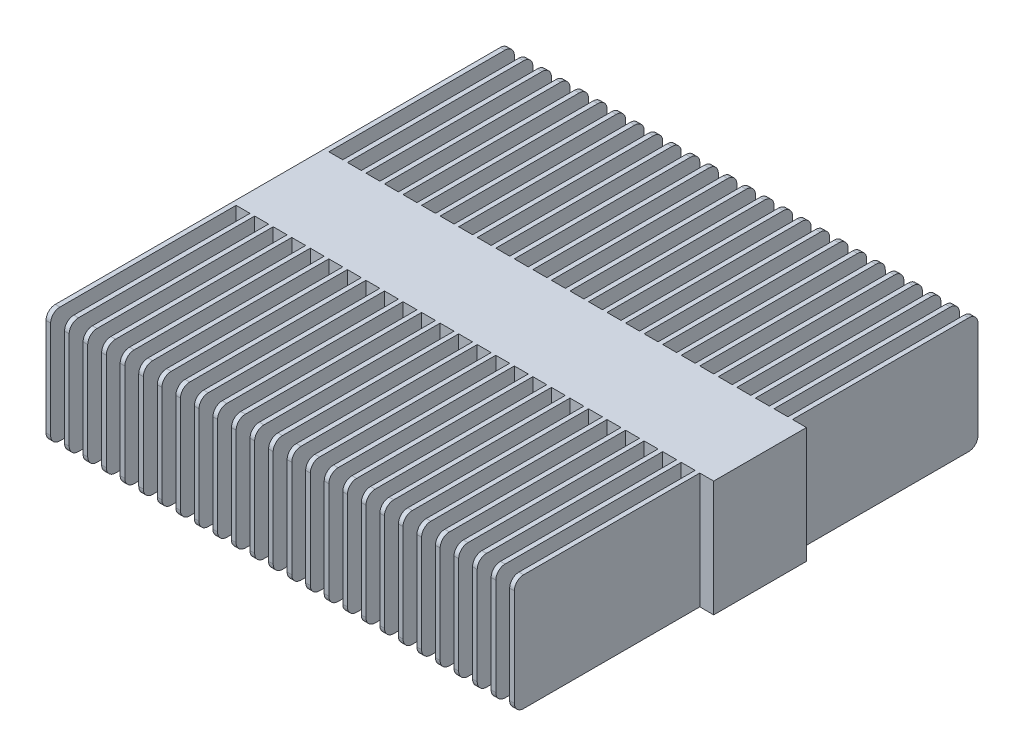
SolidWorks part; units mm, degrees
material "Thornel VCB-20 탄소 섬유"
ref_plane "정면" through (0, 0, 0) normal (0, 0, 1) x (1, 0, 0)
ref_plane "윗면" through (0, 0, 0) normal (0, 1, 0) x (1, 0, 0)
ref_plane "우측면" through (0, 0, 0) normal (1, 0, 0) x (0, 0, -1)
sketch "스케치1" plane through (0, 0, 0) normal (0, 0, 1) x (1, 0, 0)
  line L1 (0, 0) -> (104, 0)
  line L2 (0, 0) -> (0, 25)
  line L3 (0, 25) -> (104, 25)
  line L4 (104, 0) -> (104, 25)
  dimension "D1" = 25
  dimension "D2" = 104
extrude "보스-돌출1" add sketch "스케치1" along normal blind 100
fillet "필렛1" radius 2 4 edges at (52, 0, 0) (52, 25, 0) (52, 0, 100) (52, 25, 100)
sketch "스케치2" plane through (0, 0, 100) normal (0, 0, 1) x (1, 0, 0)
  line L0 (0, 25) -> (104, 25) construction
  line L1 (1, 25) -> (4, 25)
  line L2 (1, 25) -> (1, 0)
  line L3 (1, 0) -> (4, 0)
  line L4 (4, 25) -> (4, 0)
  line L5 (104, 0) -> (0, 0) construction
  line L6 (0, 23) -> (0, 2) construction
  line L7 (8, 25) -> (8, 0)
  line L8 (5, 25) -> (8, 25)
  line L9 (5, 25) -> (5, 0)
  line L10 (5, 0) -> (8, 0)
  line L11 (12, 25) -> (12, 0)
  line L12 (9, 25) -> (12, 25)
  line L13 (9, 25) -> (9, 0)
  line L14 (9, 0) -> (12, 0)
  line L15 (16, 25) -> (16, 0)
  line L16 (13, 25) -> (16, 25)
  line L17 (13, 25) -> (13, 0)
  line L18 (13, 0) -> (16, 0)
  line L19 (20, 25) -> (20, 0)
  line L20 (17, 25) -> (20, 25)
  line L21 (17, 25) -> (17, 0)
  line L22 (17, 0) -> (20, 0)
  line L23 (24, 25) -> (24, 0)
  line L24 (21, 25) -> (24, 25)
  line L25 (21, 25) -> (21, 0)
  line L26 (21, 0) -> (24, 0)
  line L27 (28, 25) -> (28, 0)
  line L28 (25, 25) -> (28, 25)
  line L29 (25, 25) -> (25, 0)
  line L30 (25, 0) -> (28, 0)
  line L31 (32, 25) -> (32, 0)
  line L32 (29, 25) -> (32, 25)
  line L33 (29, 25) -> (29, 0)
  line L34 (29, 0) -> (32, 0)
  line L35 (36, 25) -> (36, 0)
  line L36 (33, 25) -> (36, 25)
  line L37 (33, 25) -> (33, 0)
  line L38 (33, 0) -> (36, 0)
  line L39 (40, 25) -> (40, 0)
  line L40 (37, 25) -> (40, 25)
  line L41 (37, 25) -> (37, 0)
  line L42 (37, 0) -> (40, 0)
  line L43 (44, 25) -> (44, 0)
  line L44 (41, 25) -> (44, 25)
  line L45 (41, 25) -> (41, 0)
  line L46 (41, 0) -> (44, 0)
  line L47 (48, 25) -> (48, 0)
  line L48 (45, 25) -> (48, 25)
  line L49 (45, 25) -> (45, 0)
  line L50 (45, 0) -> (48, 0)
  line L51 (52, 25) -> (52, 0)
  line L52 (49, 25) -> (52, 25)
  line L53 (49, 25) -> (49, 0)
  line L54 (49, 0) -> (52, 0)
  line L55 (56, 25) -> (56, 0)
  line L56 (53, 25) -> (56, 25)
  line L57 (53, 25) -> (53, 0)
  line L58 (53, 0) -> (56, 0)
  line L59 (60, 25) -> (60, 0)
  line L60 (57, 25) -> (60, 25)
  line L61 (57, 25) -> (57, 0)
  line L62 (57, 0) -> (60, 0)
  line L63 (64, 25) -> (64, 0)
  line L64 (61, 25) -> (64, 25)
  line L65 (61, 25) -> (61, 0)
  line L66 (61, 0) -> (64, 0)
  line L67 (68, 25) -> (68, 0)
  line L68 (65, 25) -> (68, 25)
  line L69 (65, 25) -> (65, 0)
  line L70 (65, 0) -> (68, 0)
  line L71 (72, 25) -> (72, 0)
  line L72 (69, 25) -> (72, 25)
  line L73 (69, 25) -> (69, 0)
  line L74 (69, 0) -> (72, 0)
  line L75 (76, 25) -> (76, 0)
  line L76 (73, 25) -> (76, 25)
  line L77 (73, 25) -> (73, 0)
  line L78 (73, 0) -> (76, 0)
  line L79 (80, 25) -> (80, 0)
  line L80 (77, 25) -> (80, 25)
  line L81 (77, 25) -> (77, 0)
  line L82 (77, 0) -> (80, 0)
  line L83 (84, 25) -> (84, 0)
  line L84 (81, 25) -> (84, 25)
  line L85 (81, 25) -> (81, 0)
  line L86 (81, 0) -> (84, 0)
  line L87 (88, 25) -> (88, 0)
  line L88 (85, 25) -> (88, 25)
  line L89 (85, 25) -> (85, 0)
  line L90 (85, 0) -> (88, 0)
  line L91 (92, 25) -> (92, 0)
  line L92 (89, 25) -> (92, 25)
  line L93 (89, 25) -> (89, 0)
  line L94 (89, 0) -> (92, 0)
  line L95 (96, 25) -> (96, 0)
  line L96 (93, 25) -> (96, 25)
  line L97 (93, 25) -> (93, 0)
  line L98 (93, 0) -> (96, 0)
  line L99 (100, 25) -> (100, 0)
  line L100 (97, 25) -> (100, 25)
  line L101 (97, 25) -> (97, 0)
  line L102 (97, 0) -> (100, 0)
  line L103 (104, 25) -> (104, 0)
  line L104 (101, 25) -> (104, 25)
  line L105 (101, 25) -> (101, 0)
  line L106 (101, 0) -> (104, 0)
  dimension "D1" = 3
  dimension "D2" = 1
  dimension "D3" = 26
extrude "컷-돌출1" cut sketch "스케치2" against normal blind 40
sketch "스케치3" plane through (0, 0, 0) normal (0, 0, -1) x (-1, 0, 0)
  line L0 (0, 23) -> (0, 2) construction
  line L1 (-4, 25) -> (-1, 25)
  line L2 (-4, 25) -> (-4, 0)
  line L3 (-4, 0) -> (-1, 0)
  line L4 (-1, 25) -> (-1, 0)
  line L5 (-104, 25) -> (0, 25) construction
  line L6 (0, 0) -> (-104, 0) construction
  line L7 (-8, 25) -> (-5, 25)
  line L8 (-8, 25) -> (-8, 0)
  line L9 (-5, 25) -> (-5, 0)
  line L10 (-8, 0) -> (-5, 0)
  line L11 (-12, 25) -> (-9, 25)
  line L12 (-12, 25) -> (-12, 0)
  line L13 (-9, 25) -> (-9, 0)
  line L14 (-12, 0) -> (-9, 0)
  line L15 (-16, 25) -> (-13, 25)
  line L16 (-16, 25) -> (-16, 0)
  line L17 (-13, 25) -> (-13, 0)
  line L18 (-16, 0) -> (-13, 0)
  line L19 (-20, 25) -> (-17, 25)
  line L20 (-20, 25) -> (-20, 0)
  line L21 (-17, 25) -> (-17, 0)
  line L22 (-20, 0) -> (-17, 0)
  line L23 (-24, 25) -> (-21, 25)
  line L24 (-24, 25) -> (-24, 0)
  line L25 (-21, 25) -> (-21, 0)
  line L26 (-24, 0) -> (-21, 0)
  line L27 (-28, 25) -> (-25, 25)
  line L28 (-28, 25) -> (-28, 0)
  line L29 (-25, 25) -> (-25, 0)
  line L30 (-28, 0) -> (-25, 0)
  line L31 (-32, 25) -> (-29, 25)
  line L32 (-32, 25) -> (-32, 0)
  line L33 (-29, 25) -> (-29, 0)
  line L34 (-32, 0) -> (-29, 0)
  line L35 (-36, 25) -> (-33, 25)
  line L36 (-36, 25) -> (-36, 0)
  line L37 (-33, 25) -> (-33, 0)
  line L38 (-36, 0) -> (-33, 0)
  line L39 (-40, 25) -> (-37, 25)
  line L40 (-40, 25) -> (-40, 0)
  line L41 (-37, 25) -> (-37, 0)
  line L42 (-40, 0) -> (-37, 0)
  line L43 (-44, 25) -> (-41, 25)
  line L44 (-44, 25) -> (-44, 0)
  line L45 (-41, 25) -> (-41, 0)
  line L46 (-44, 0) -> (-41, 0)
  line L47 (-48, 25) -> (-45, 25)
  line L48 (-48, 25) -> (-48, 0)
  line L49 (-45, 25) -> (-45, 0)
  line L50 (-48, 0) -> (-45, 0)
  line L51 (-52, 25) -> (-49, 25)
  line L52 (-52, 25) -> (-52, 0)
  line L53 (-49, 25) -> (-49, 0)
  line L54 (-52, 0) -> (-49, 0)
  line L55 (-56, 25) -> (-53, 25)
  line L56 (-56, 25) -> (-56, 0)
  line L57 (-53, 25) -> (-53, 0)
  line L58 (-56, 0) -> (-53, 0)
  line L59 (-60, 25) -> (-57, 25)
  line L60 (-60, 25) -> (-60, 0)
  line L61 (-57, 25) -> (-57, 0)
  line L62 (-60, 0) -> (-57, 0)
  line L63 (-64, 25) -> (-61, 25)
  line L64 (-64, 25) -> (-64, 0)
  line L65 (-61, 25) -> (-61, 0)
  line L66 (-64, 0) -> (-61, 0)
  line L67 (-68, 25) -> (-65, 25)
  line L68 (-68, 25) -> (-68, 0)
  line L69 (-65, 25) -> (-65, 0)
  line L70 (-68, 0) -> (-65, 0)
  line L71 (-72, 25) -> (-69, 25)
  line L72 (-72, 25) -> (-72, 0)
  line L73 (-69, 25) -> (-69, 0)
  line L74 (-72, 0) -> (-69, 0)
  line L75 (-76, 25) -> (-73, 25)
  line L76 (-76, 25) -> (-76, 0)
  line L77 (-73, 25) -> (-73, 0)
  line L78 (-76, 0) -> (-73, 0)
  line L79 (-80, 25) -> (-77, 25)
  line L80 (-80, 25) -> (-80, 0)
  line L81 (-77, 25) -> (-77, 0)
  line L82 (-80, 0) -> (-77, 0)
  line L83 (-84, 25) -> (-81, 25)
  line L84 (-84, 25) -> (-84, 0)
  line L85 (-81, 25) -> (-81, 0)
  line L86 (-84, 0) -> (-81, 0)
  line L87 (-88, 25) -> (-85, 25)
  line L88 (-88, 25) -> (-88, 0)
  line L89 (-85, 25) -> (-85, 0)
  line L90 (-88, 0) -> (-85, 0)
  line L91 (-92, 25) -> (-89, 25)
  line L92 (-92, 25) -> (-92, 0)
  line L93 (-89, 25) -> (-89, 0)
  line L94 (-92, 0) -> (-89, 0)
  line L95 (-96, 25) -> (-93, 25)
  line L96 (-96, 25) -> (-96, 0)
  line L97 (-93, 25) -> (-93, 0)
  line L98 (-96, 0) -> (-93, 0)
  line L99 (-100, 25) -> (-97, 25)
  line L100 (-100, 25) -> (-100, 0)
  line L101 (-97, 25) -> (-97, 0)
  line L102 (-100, 0) -> (-97, 0)
  line L103 (-104, 25) -> (-101, 25)
  line L104 (-104, 25) -> (-104, 0)
  line L105 (-101, 25) -> (-101, 0)
  line L106 (-104, 0) -> (-101, 0)
  dimension "D1" = 3
  dimension "D2" = 1
  dimension "D3" = 26
extrude "컷-돌출2" cut sketch "스케치3" against normal blind 40
